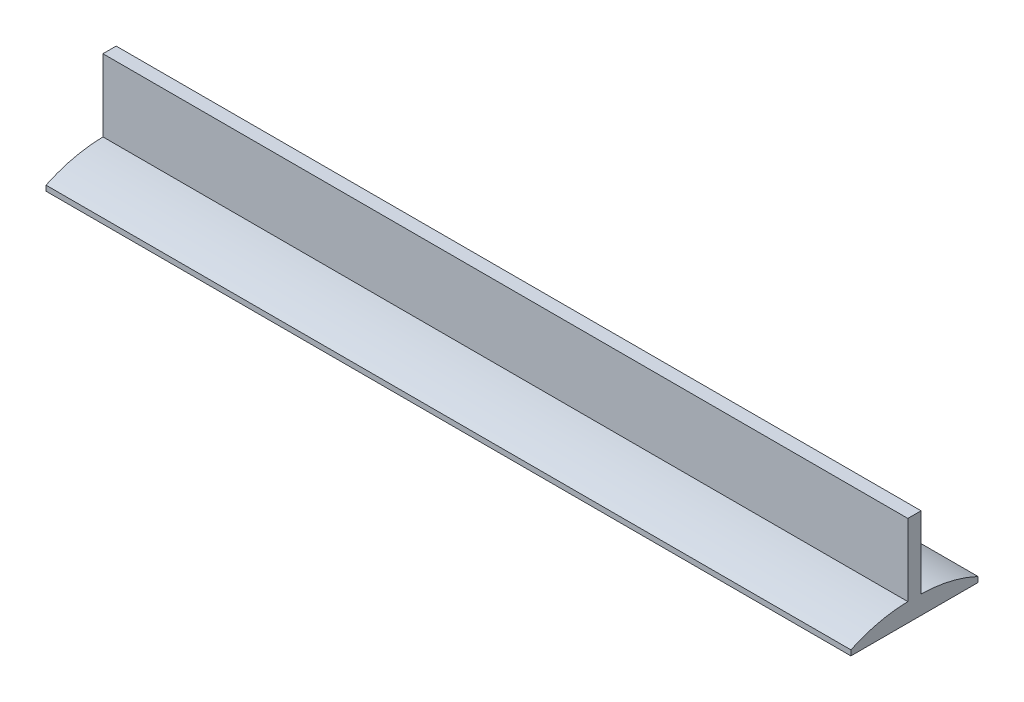
SolidWorks part; units mm, degrees
ref_plane "Front Plane" through (0, 0, 0) normal (0, 0, 1) x (1, 0, 0)
ref_plane "Top Plane" through (0, 0, 0) normal (0, 1, 0) x (1, 0, 0)
ref_plane "Right Plane" through (0, 0, 0) normal (1, 0, 0) x (0, 0, -1)
sketch "Sketch1" plane through (0, 0, 0) normal (1, 0, 0) x (0, 0, -1)
  line L0 (0, 0) -> (59.4881, 0)
  line L1 (55, 0) -> (-55, 0) construction
  line L2 (59.4881, 0) -> (59.4881, 3.175)
  line L3 (59.4881, 3.175) -> (16.3081, 3.175)
  line L4 (16.3081, 3.175) -> (0, 3.175) construction
  line L5 (0, 55) -> (0, -55) construction
  line L6 (59.4881, 1.5875) -> (0, 1.5875) construction
  line L7 (0, 0) -> (0, 124.5585) construction
  line L8 (-3.175, -10.4951) -> (-3.175, 72.3911) construction
  line L9 (-6.35, 0) -> (-6.35, 124.5585) construction
  line L10 (-65.8381, 1.5875) -> (-6.35, 1.5875) construction
  line L11 (-22.6581, 3.175) -> (-6.35, 3.175) construction
  line L12 (-65.8381, 3.175) -> (-22.6581, 3.175)
  line L13 (-65.8381, 0) -> (-65.8381, 3.175)
  line L14 (-6.35, 0) -> (-65.8381, 0)
  line L15 (-6.35, 51.2862) -> (0, 51.2862)
  line L16 (-6.35, 0) -> (0, 0)
  arc A0 (16.3081, 3.175) -> (0, 51.2862) centre (-67.4969, 1.5875) ccw
  arc A1 (-22.6581, 3.175) -> (-6.35, 51.2862) centre (61.1469, 1.5875) cw
  dimension "D2" = 83.82
  dimension "D1" = 3.175
  dimension "D3" = 50.8
  dimension "D4" = 43.18
  dimension "D5" = 6.35
extrude "Boss-Extrude1" [suppressed] add sketch "Sketch1" against normal blind 482.6
sketch "Sketch2" plane through (0, 0, 0) normal (1, 0, 0) x (0, 0, -1)
  line L0 (0, 0) -> (0, 54.3465)
  line L1 (0, 55) -> (0, -55) construction
  line L2 (0, 54.3465) -> (3.9688, 54.3465)
  line L3 (3.9688, 54.3465) -> (3.9688, 11.1515)
  line L4 (0, 0) -> (38.1, 0)
  line L5 (55, 0) -> (-55, 0) construction
  line L6 (38.1, 0) -> (38.1, 3.175)
  line L7 (0.7937, 61.624) -> (0.7938, -152.4777) construction
  line L8 (2.3812, 62.5054) -> (2.3813, -144.1659) construction
  line L9 (0.7937, 57.434) -> (3.9687, 57.434) construction
  line L10 (2.3813, 11.1665) -> (27.3868, 11.1665) construction
  arc A0 (3.9688, 11.1515) -> (38.1, 3.175) centre (2.3813, -72.6535) cw
  arc A1 (3.9688, 11.1515) -> (2.3813, 11.1665) centre (2.3813, -72.6535) ccw construction
  point P18 (2.3812, 57.434)
  point P20 (3.9688, 10.1018)
  point P21 (3.9688, 57.434)
  point P23 (2.3813, 71.138)
  point P24 (0.7937, 68.1217)
  point P25 (0.7937, 61.624)
  point P26 (2.3813, 62.5054)
  dimension "D6" = 83.82
  dimension "D1" = 38.1
  dimension "D2" = 127
  dimension "D3" = 3.9688
  dimension "D4" = 3.175
  dimension "D5" = 3.175
extrude "Boss-Extrude2" add sketch "Sketch2" against normal blind 482.6
mirror "Mirror1" about plane through (-482.6, 0, 0) normal (0, 0, 1) of "Boss-Extrude2"
